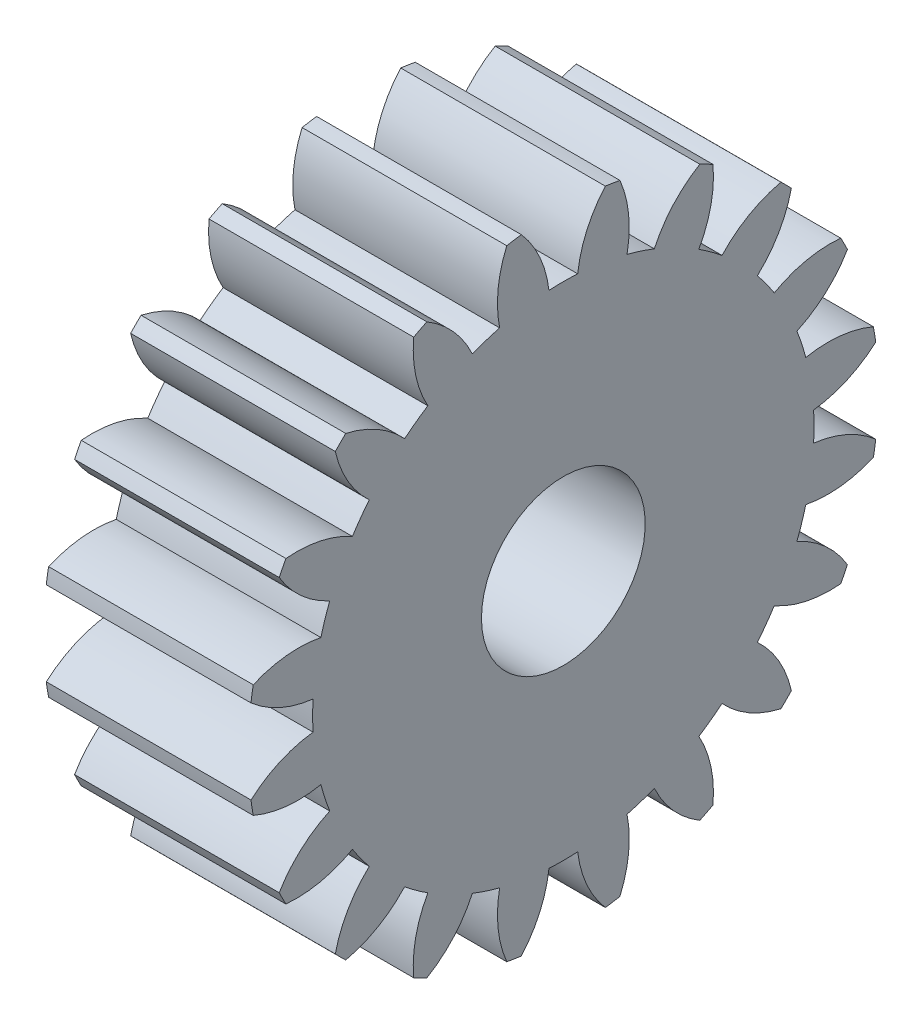
SolidWorks part; units mm, degrees
ref_plane "Plane1" through (0, 0, 0) normal (0, 0, 1) x (1, 0, 0)
ref_plane "Plane2" through (0, 0, 0) normal (0, 1, 0) x (1, 0, 0)
ref_plane "Plane3" through (0, 0, 0) normal (1, 0, 0) x (0, 0, -1)
other "Configuration Table"
sketch "HoldingSke" plane through (0, 0, 0) normal (0, 1, 0) x (1, 0, 0)
  line L0 (0, 0) -> (1.3424, -0.4886)
  line L1 (-15, 0) -> (100, 0) construction
  line L2 (0, 0) -> (-2.1039, 2.3779)
  line L3 (0, 0) -> (-11.863, 4.5341)
  line L4 (0, 0) -> (8.1152, 2.9537)
  line L5 (0, 0) -> (-46.8476, -17.4728)
  line L6 (0, 0) -> (-4.1448, -2.7965)
  line L7 (-2.1039, 2.3779) -> (8.6586, 51.2059)
  line L8 (-76.2, 54.61) -> (-75.5, 54.61)
  line L9 (-71.009, 38.7566) -> (-53.1078, 45.2721)
  line L10 (-76.2, 71.12) -> (104.1128, 71.12)
  line L11 (0, 0) -> (-5, 0)
  line L12 (-76.2, 101.6) -> (-76.173, 101.6)
  line L13 (24.9733, 27.94) -> (52.9518, 28.4284)
  line L14 (24.9733, 27.94) -> (24.9743, 27.94)
  line L15 (24.9733, 27.94) -> (100.4006, 29.5858)
  line L16 (-63.627, -0.7) -> (-12.827, -0.7)
  circle A0 centre (0, 0) radius 2
  circle A1 centre (0, 0) radius 6.124
  circle A2 centre (0, 0) radius 37.5
  circle A3 centre (0, 0) radius 2
  dimension "MHD" = 12.248
  dimension "Hub_dia" = 75
  dimension "Bore" = 4
  dimension "MBD" = 4
  dimension "Num_teeth" = 20
  dimension "Pitch" = 1.4286
  dimension "Overall_len" = 50
  dimension "Show_teeth" = 20
  dimension "Thickness" = 5
  dimension "OAL" = 50.0001
  dimension "T_dim" = 0.7
  dimension "Ap" = 20
  dimension "H" = 19.05
  dimension "Pitch_radius" = 180.3128
  dimension "Width" = 5
  dimension "Backlash" = 0.027
  dimension "Addendum_fac" = 1
  dimension "Dedendum_fac" = 1.25
  dimension "Clearance_fac" = 0.25
  dimension "Dedendum_add" = 0.001
  dimension "Module" = 0.7
sketch "BasProSke" plane through (0, 0, 0) normal (0, 1, 0) x (1, 0, 0)
  line L0 (-10, 0) -> (60, 0) construction
  line L1 (0, 0) -> (0, 7.7)
  line L2 (0, 0) -> (5, 0)
  line L3 (5, 0) -> (5, 7.7)
  line L4 (5, 7.7) -> (0, 7.7)
  dimension "Thickness" = 5
  dimension "Diameter" = 15.4
revolve "Base-Revolve" add sketch "BasProSke" angle 360 about L0
sketch "TooCutSke" plane through (0, 0, 0) normal (1, 0, 0) x (0, 0, -1)
  line L1 (0, 0) -> (0, 107) construction
  line L2 (0, 0) -> (-0.5964, 6.9745) construction
  line L3 (0, 0) -> (-2.1844, 13.792) construction
  line L4 (-0.5964, 6.9745) -> (-1.0922, 6.896) construction
  arc A0 (0.3505, 6.114) -> (-0.3505, 6.114) centre (0, 0) ccw
  arc A1 (1.0465, 7.6542) -> (-1.0465, 7.6542) centre (0, 0) ccw
  circle A2 centre (0, 0) radius 7 construction
  circle A3 centre (0, 0) radius 6.5778 construction
  arc A4 (-0.3505, 6.114) -> (-1.0465, 7.6542) centre (-3.1311, 5.7848) ccw
  arc A5 (1.0465, 7.6542) -> (0.3505, 6.114) centre (3.1311, 5.7848) ccw
  dimension "Root_dia" = 12.248
  dimension "Overcut_dia" = 15.4508
  dimension "Pitch_dia" = 14
  dimension "Base_dia" = 13.1557
  dimension "Flank_rad" = 2.8
  dimension "Half_ang" = 9
  dimension "Half_CT" = 0.502
extrude "ToothCut" cut sketch "TooCutSke" along normal through all
fillet "Breaks" [suppressed] radius 0.014
fillet "RootFillets" [suppressed] radius 0.176
pattern_circular "TeethCuts" count 20 every 18 about axis through (-10, 0, 0) along (1, 0, 0) of "ToothCut", "RootFillets", "Breaks"
sketch "HubNeaOneSke" plane through (0, 0, 0) normal (-1, 0, 0) x (0, 0, 1)
  circle A0 centre (0, 0) radius 6.124
  dimension "Diameter" = 12.248
extrude "HubNearOne" [suppressed] add sketch "HubNeaOneSke" along normal blind 45.0001
sketch "HubNeaBotSke" plane through (0, 0, 0) normal (-1, 0, 0) x (0, 0, 1)
  circle A0 centre (0, 0) radius 6.124
  dimension "Diameter" = 12.248
extrude "HubNearBoth" [suppressed] add sketch "HubNeaBotSke" along normal blind 22.5
ref_plane "FarPln" through (5, 0, 0) normal (1, 0, 0) x (0, 0, -1)
sketch "HubFarSke" plane through (5, 0, 0) normal (1, 0, 0) x (0, 0, -1)
  circle A0 centre (0, 0) radius 6.124
  dimension "Diameter" = 12.248
extrude "HubFar" [suppressed] add sketch "HubFarSke" along normal blind 22.5
sketch "BorSke" plane through (0, 0, 0) normal (1, 0, 0) x (0, 0, -1)
  circle A0 centre (0, 0) radius 2
  dimension "Diameter" = 4
extrude "Bore" cut sketch "BorSke" along normal mid plane 100.0001
sketch "KeySke" plane through (0, 0, 0) normal (1, 0, 0) x (0, 0, -1)
  line L0 (-0.8, 0) -> (-0.8, 2.7)
  line L1 (-0.8, 2.7) -> (0.8, 2.7)
  line L2 (0.8, 2.7) -> (0.8, 0)
  line L3 (0, 0) -> (0, 34) construction
  line L4 (-0.8, 0) -> (0.8, 0)
  dimension "Offset" = 2.7
  dimension "Width" = 1.6
extrude "Keyway" [suppressed] cut sketch "KeySke" along normal mid plane 100.0001
pattern_circular "Keyway2" [suppressed] count 2 every 90 about axis through (-10, 0, 0) along (1, 0, 0)
equation "' \"Module@HoldingSke\" = 6.35"
equation "' \"Num_teeth@HoldingSke\" = 12"
equation "' \"Ap@HoldingSke\" =  20"
equation "' \"Ap@HoldingSke\" = 20"
equation "' \"Width@HoldingSke\" = 0.5 * 25.4"
equation "' \"Hub_dia@HoldingSke\"= 1 * 25.4"
equation "' \"Hub_dia@HoldingSke\" = 1 * 25.4"
equation "' \"Overall_len@HoldingSke\" = 1.0 * 25.4"
equation "' \"Bore@HoldingSke\" = 0.75 * 25.4"
equation "' \"T_dim@HoldingSke\" = 0.1 * 25.4"
equation "' \"Width@KeySke\" = 0.25 * 25.4"
equation "' \"Show_teeth@HoldingSke\" = 13"
equation "' \"Backlash@HoldingSke\" = 0.009 * 25.4"
equation "' \"Addendum_fac@HoldingSke\" = 1.0"
equation "' \"Dedendum_fac@HoldingSke\" = 1.25"
equation "' \"Dedendum_add@HoldingSke\" = 0.00005 * 25.4"
equation "' \"Clearance_fac@HoldingSke\" = 0.25"
equation "\"Pitch@HoldingSke\" = 1 / \"Module@HoldingSke\""
equation "\"Overcut_dia@TooCutSke\" = (\"Num_teeth@HoldingSke\" + 2 * \"Addendum_fac@HoldingSke\") / \"Pitch@HoldingSke\" + 0.002 * 25.4"
equation "\"Pitch_dia@TooCutSke\" = \"Num_teeth@HoldingSke\" / \"Pitch@HoldingSke\""
equation "\"Base_dia@TooCutSke\" = \"Num_teeth@HoldingSke\" / \"Pitch@HoldingSke\" * cos((\"Ap@HoldingSke\"  * 3.14159265 / 180))"
equation "\"Root_dia@TooCutSke\" = (\"Num_teeth@HoldingSke\" + 2) / \"Pitch@HoldingSke\" - 2 * (\"Addendum_fac@HoldingSke\" + \"Dedendum_fac@HoldingSke\") / \"Pitch@HoldingSke\" - \"Dedendum_add@HoldingSke\" * 2"
equation "\"Half_ang@TooCutSke\" = 180 / \"Num_teeth@HoldingSke\""
equation "\"Half_CT@TooCutSke\" = \"Num_teeth@HoldingSke\" / \"Pitch@HoldingSke\" * sin((3.14159265 / 2 / \"Num_teeth@HoldingSke\")) / 2 - 7 * \"Backlash@HoldingSke\" / 4"
equation "\"Flank_rad@TooCutSke\" = \"Num_teeth@HoldingSke\" / \"Pitch@HoldingSke\" / 5"
equation "\"Radius@RootFillets\" = \"Clearance_fac@HoldingSke\" / \"Pitch@HoldingSke\" + \"Dedendum_add@HoldingSke\""
equation "\"Break_rad@Breaks\" = 0.02 / \"Pitch@HoldingSke\""
equation "\"Thickness@HoldingSke\" = \"Width@HoldingSke\""
equation "\"OAL@HoldingSke\" = \"Thickness@HoldingSke\""
equation "\"MHD@HoldingSke\" = (\"Num_teeth@HoldingSke\" + 2) / \"Pitch@HoldingSke\" - 2 * (\"Addendum_fac@HoldingSke\" + \"Dedendum_fac@HoldingSke\")  / \"Pitch@HoldingSke\" - \"Dedendum_add@HoldingSke\" * 2"
equation "\"MBD@HoldingSke\" = (\"Num_teeth@HoldingSke\" + 2) / \"Pitch@HoldingSke\" - 2 * (\"Addendum_fac@HoldingSke\" + \"Dedendum_fac@HoldingSke\")  / \"Pitch@HoldingSke\" - \"Dedendum_add@HoldingSke\" * 2 - 0.002 * 25.4"
equation "\"MHD@HoldingSke\" = ((sgn( \"MHD@HoldingSke\" - \"Hub_dia@HoldingSke\" )-1)*( \"MHD@HoldingSke\" - \"Hub_dia@HoldingSke\" ))/-2+ \"Hub_dia@HoldingSke\""
equation "\"MBD@HoldingSke\" = ((sgn( \"MBD@HoldingSke\" - \"Bore@HoldingSke\" )-1)*( \"MBD@HoldingSke\" - \"Bore@HoldingSke\" ))/-2+ \"Bore@HoldingSke\""
equation "\"OAL@HoldingSke\" = ((sgn( \"OAL@HoldingSke\" - \"Overall_len@HoldingSke\" )+1)*( \"OAL@HoldingSke\" - \"Overall_len@HoldingSke\" ))/2 + \"Overall_len@HoldingSke\" + 0.000002 * 25.4"
equation "\"Num_teeth@TeethCuts\" = int( \"Show_teeth@HoldingSke\" ) + 1"
equation "\"Num_teeth@TeethCuts\" = ((sgn( \"Num_teeth@TeethCuts\" - \"Num_teeth@HoldingSke\" )-1)*( \"Num_teeth@TeethCuts\" - \"Num_teeth@HoldingSke\" ))/-2+ \"Num_teeth@HoldingSke\""
equation "\"Num_teeth@TeethCuts\" = ((sgn( \"Num_teeth@TeethCuts\" - 2.0)+1)*( \"Num_teeth@TeethCuts\" - 2.0))/2 +2.0"
equation "\"Angle@TeethCuts\" = 360.0 / \"Num_teeth@HoldingSke\""
equation "\"Diameter@BasProSke\" = (\"Num_teeth@HoldingSke\" + 2 * \"Addendum_fac@HoldingSke\") / \"Pitch@HoldingSke\""
equation "\"Thickness@BasProSke\"  = \"Thickness@HoldingSke\""
equation "' \"Fillet_rad@BasProSke\" =  \"Thickness@HoldingSke\" * 0.05"
equation "' \"Fillet_rad@BasProSke\" = \"Thickness@HoldingSke\" * 0.05"
equation "\"MHD@HoldingSke\" = ((sgn( \"MHD@HoldingSke\" - \"Root_dia@TooCutSke\" )-1)*( \"MHD@HoldingSke\" - \"Root_dia@TooCutSke\" ))/-2+ \"Root_dia@TooCutSke\""
equation "\"Diameter@HubNeaOneSke\" = \"MHD@HoldingSke\""
equation "\"Length@HubNearOne\" = \"OAL@HoldingSke\" - \"Thickness@BasProSke\""
equation "\"Diameter@HubNeaBotSke\" = \"MHD@HoldingSke\""
equation "\"Length@HubNearBoth\" = ( \"OAL@HoldingSke\" - \"Thickness@BasProSke\" ) / 2.0"
equation "\"Thickness@FarPln\" = \"Thickness@BasProSke\""
equation "\"Diameter@HubFarSke\" = \"MHD@HoldingSke\""
equation "\"Length@HubFar\" = ( \"OAL@HoldingSke\" - \"Thickness@BasProSke\" ) / 2.0"
equation "\"Diameter@BorSke\" = \"MBD@HoldingSke\""
equation "\"D1@Bore\" = \"OAL@HoldingSke\" * 2.0"
equation "\"D1@Keyway\" = \"OAL@HoldingSke\" * 2.0"
equation "\"Offset@KeySke\" = \"T_dim@HoldingSke\" + \"MBD@HoldingSke\" / 2.0"
